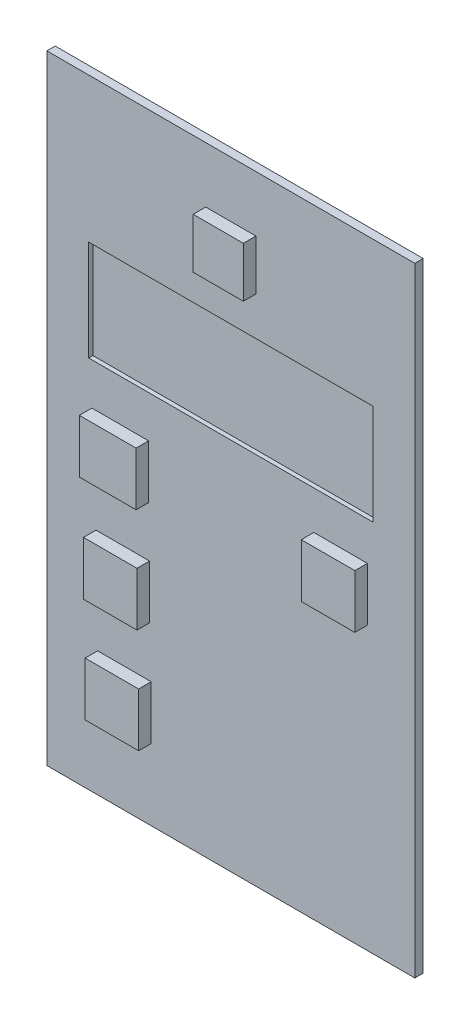
SolidWorks part; units mm, degrees
ref_plane "Front Plane" through (0, 0, 0) normal (0, 0, 1) x (1, 0, 0)
ref_plane "Top Plane" through (0, 0, 0) normal (0, 1, 0) x (1, 0, 0)
ref_plane "Right Plane" through (0, 0, 0) normal (1, 0, 0) x (0, 0, -1)
sketch "Sketch1" plane through (0, 0, 0) normal (0, 0, 1) x (1, 0, 0)
  line L1 (0, 0) -> (44, 0)
  line L2 (0, 0) -> (0, 74)
  line L3 (0, 74) -> (44, 74)
  line L4 (44, 0) -> (44, 74)
  dimension "D1" = 74
  dimension "D2" = 44
extrude "Boss-Extrude1" add sketch "Sketch1" along normal blind 1
sketch "Sketch2" plane through (0, 0, 1) normal (0, 0, 1) x (1, 0, 0)
  line L0 (44, 0) -> (44, 74) construction
  line L1 (5, 56.7036) -> (39, 56.7036)
  line L2 (5, 56.7036) -> (5, 44.7036)
  line L3 (5, 44.7036) -> (39, 44.7036)
  line L4 (39, 56.7036) -> (39, 44.7036)
  dimension "D1" = 34
  dimension "D2" = 5
  dimension "D3" = 12
extrude "Cut-Extrude1" cut sketch "Sketch2" against normal blind 0.5
sketch "Sketch3" plane through (0, 0, 1) normal (0, 0, 1) x (1, 0, 0)
  line L0 (44, 0) -> (44, 74) construction
  line L1 (19, 67.3224) -> (25, 67.3224)
  line L2 (19, 67.3224) -> (19, 61.3224)
  line L3 (19, 61.3224) -> (25, 61.3224)
  line L4 (25, 67.3224) -> (25, 61.3224)
  dimension "D1" = 6
  dimension "D2" = 6
  dimension "D3" = 19
extrude "Boss-Extrude2" add sketch "Sketch3" along normal blind 1.5
sketch "Sketch4" plane through (0, 0, 2.5) normal (0, 0, 1) x (1, 0, 0)
  line L1 (19.1965, 67.3688) -> (25.1965, 67.3688)
  line L2 (19.1965, 67.3688) -> (19.1965, 61.3688)
  line L3 (19.1965, 61.3688) -> (25.1965, 61.3688)
  line L4 (25.1965, 67.3688) -> (25.1965, 61.3688)
  dimension "D1" = 6
  dimension "D2" = 6
sketch "Sketch5" plane through (0, 0, 1) normal (0, 0, 1) x (1, 0, 0)
  line L1 (5.392, 39.7025) -> (12.1728, 39.7025)
  line L2 (5.392, 39.7025) -> (5.392, 33.3148)
  line L3 (5.392, 33.3148) -> (12.1728, 33.3148)
  line L4 (12.1728, 39.7025) -> (12.1728, 33.3148)
extrude "Boss-Extrude5" add sketch "Sketch5" along normal blind 1.5
sketch "Sketch7" plane through (0, 0, 1) normal (0, 0, 1) x (1, 0, 0)
  line L0 (5.392, 33.3148) -> (12.1728, 33.3148) construction
  line L1 (5.8834, 27.3148) -> (12.2834, 27.3148)
  line L2 (5.8834, 27.3148) -> (5.8834, 20.9148)
  line L3 (5.8834, 20.9148) -> (12.2834, 20.9148)
  line L4 (12.2834, 27.3148) -> (12.2834, 20.9148)
  dimension "D1" = 6.4
  dimension "D2" = 6.4
  dimension "D3" = 6
extrude "Boss-Extrude6" add sketch "Sketch7" along normal blind 1.5
sketch "Sketch8" plane through (0, 0, 1) normal (0, 0, 1) x (1, 0, 0)
  line L0 (5.8834, 20.9148) -> (12.2834, 20.9148) construction
  line L1 (6.0799, 14.9148) -> (12.4799, 14.9148)
  line L2 (6.0799, 14.9148) -> (6.0799, 8.5148)
  line L3 (6.0799, 8.5148) -> (12.4799, 8.5148)
  line L4 (12.4799, 14.9148) -> (12.4799, 8.5148)
  dimension "D1" = 6.4
  dimension "D2" = 6.4
  dimension "D3" = 6
extrude "Boss-Extrude7" add sketch "Sketch8" along normal blind 1.5
sketch "Sketch9" plane through (0, 0, 1) normal (0, 0, 1) x (1, 0, 0)
  line L1 (38.3255, 40.0956) -> (31.9255, 40.0956)
  line L2 (38.3255, 40.0956) -> (38.3255, 33.6956)
  line L3 (38.3255, 33.6956) -> (31.9255, 33.6956)
  line L4 (31.9255, 40.0956) -> (31.9255, 33.6956)
  dimension "D1" = 6.4
  dimension "D2" = 6.4
extrude "Boss-Extrude8" add sketch "Sketch9" along normal blind 1.5
